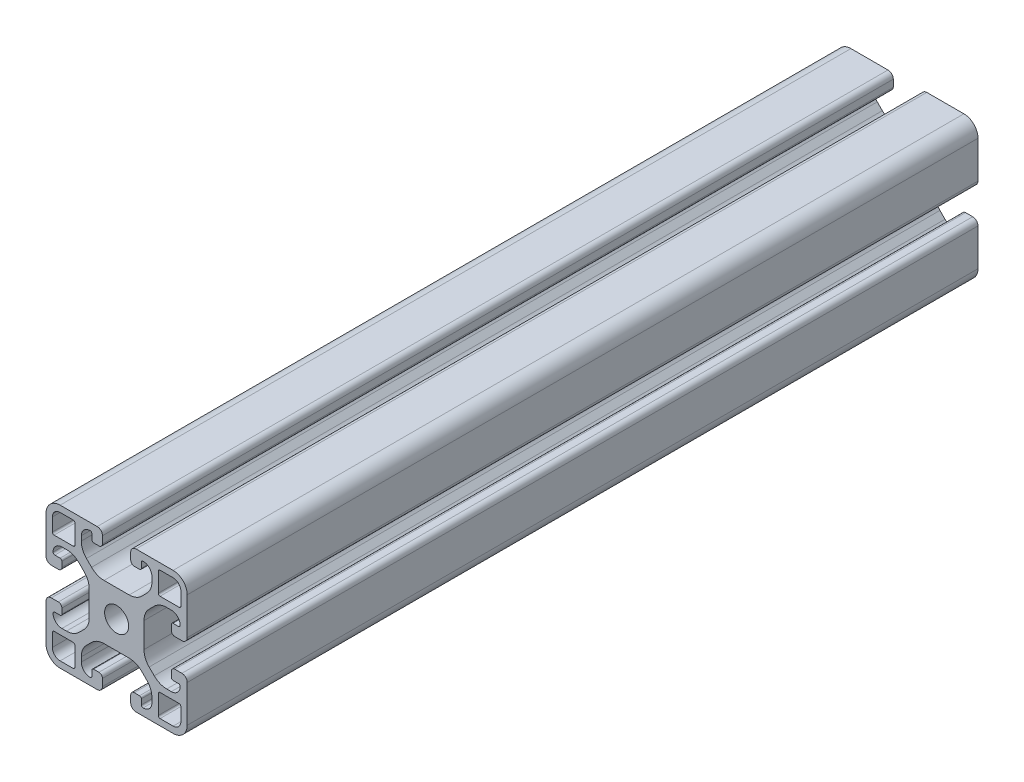
SolidWorks part; units mm, degrees
material "Alliage 1060"
ref_plane "Plan de face" through (0, 0, 0) normal (0, 0, 1) x (1, 0, 0)
ref_plane "Plan de dessus" through (0, 0, 0) normal (0, 1, 0) x (1, 0, 0)
ref_plane "Plan de droite" through (0, 0, 0) normal (1, 0, 0) x (0, 0, -1)
ref_plane "Plan1" through (0, 0, 20) normal (0, 0, 1) x (1, 0, 0)
sketch "Esquisse1" plane through (0, 0, 20) normal (0, 0, 1) x (1, 0, 0)
  line L0 (3.5, 16) -> (1.5, 16)
  line L1 (0, 14.5) -> (0, 4)
  line L2 (4, 0) -> (14.5, 0)
  line L3 (16, 1.5) -> (16, 3.5)
  line L4 (15, 4.5) -> (13.5, 4.5)
  line L5 (13, 4) -> (13, 2.5)
  line L6 (10, 4.5) -> (10, 5.8076)
  line L7 (11.4645, 9.3431) -> (12.9069, 10.7855)
  line L8 (16.4424, 12.25) -> (23.5576, 12.25)
  line L9 (27.0931, 10.7855) -> (28.5355, 9.3431)
  line L10 (30, 5.8076) -> (30, 4.5)
  line L11 (27, 2.5) -> (27, 4)
  line L12 (26.5, 4.5) -> (25, 4.5)
  line L13 (24, 3.5) -> (24, 1.5)
  line L14 (25.5, 0) -> (36, 0)
  line L15 (40, 4) -> (40, 14.5)
  line L16 (38.5, 16) -> (36.5, 16)
  line L17 (35.5, 15) -> (35.5, 13.5)
  line L18 (36, 13) -> (37.5, 13)
  line L19 (35.5, 10) -> (34.1924, 10)
  line L20 (30.6569, 11.4645) -> (29.2145, 12.9069)
  line L21 (27.75, 16.4424) -> (27.75, 23.5576)
  line L22 (29.2145, 27.0931) -> (30.6569, 28.5355)
  line L23 (34.1924, 30) -> (35.5, 30)
  line L24 (37.5, 27) -> (36, 27)
  line L25 (35.5, 26.5) -> (35.5, 25)
  line L26 (36.5, 24) -> (38.5, 24)
  line L27 (40, 25.5) -> (40, 36)
  line L28 (36, 40) -> (25.5, 40)
  line L29 (24, 38.5) -> (24, 36.5)
  line L30 (25, 35.5) -> (26.5, 35.5)
  line L31 (27, 36) -> (27, 37.5)
  line L32 (30, 35.5) -> (30, 34.1924)
  line L33 (28.5355, 30.6569) -> (27.0931, 29.2145)
  line L34 (23.5576, 27.75) -> (16.4424, 27.75)
  line L35 (12.9069, 29.2145) -> (11.4645, 30.6569)
  line L36 (10, 34.1924) -> (10, 35.5)
  line L37 (13, 37.5) -> (13, 36)
  line L38 (13.5, 35.5) -> (15, 35.5)
  line L39 (16, 36.5) -> (16, 38.5)
  line L40 (14.5, 40) -> (4, 40)
  line L41 (0, 36) -> (0, 25.5)
  line L42 (1.5, 24) -> (3.5, 24)
  line L43 (4.5, 25) -> (4.5, 26.5)
  line L44 (4, 27) -> (2.5, 27)
  line L45 (4.5, 30) -> (5.8076, 30)
  line L46 (9.3431, 28.5355) -> (10.7855, 27.0931)
  line L47 (12.25, 23.5576) -> (12.25, 16.4424)
  line L48 (10.7855, 12.9069) -> (9.3431, 11.4645)
  line L49 (5.8076, 10) -> (4.5, 10)
  line L50 (2.5, 13) -> (4, 13)
  line L51 (4.5, 13.5) -> (4.5, 15)
  line L52 (1.8, 4) -> (1.8, 7.7)
  line L53 (2.3, 8.2) -> (7.7, 8.2)
  line L54 (8.2, 7.7) -> (8.2, 2.3)
  line L55 (7.7, 1.8) -> (4, 1.8)
  line L56 (36, 1.8) -> (32.3, 1.8)
  line L57 (31.8, 2.3) -> (31.8, 7.7)
  line L58 (32.3, 8.2) -> (37.7, 8.2)
  line L59 (38.2, 7.7) -> (38.2, 4)
  line L60 (38.2, 36) -> (38.2, 32.3)
  line L61 (37.7, 31.8) -> (32.3, 31.8)
  line L62 (31.8, 32.3) -> (31.8, 37.7)
  line L63 (32.3, 38.2) -> (36, 38.2)
  line L64 (4, 38.2) -> (7.7, 38.2)
  line L65 (8.2, 37.7) -> (8.2, 32.3)
  line L66 (7.7, 31.8) -> (2.3, 31.8)
  line L67 (1.8, 32.3) -> (1.8, 36)
  arc A0 (4.5, 15) -> (3.5, 16) centre (3.5, 15) ccw
  arc A1 (1.5, 16) -> (0, 14.5) centre (1.5, 14.5) ccw
  arc A2 (0, 4) -> (4, 0) centre (4, 4) ccw
  arc A3 (14.5, 0) -> (16, 1.5) centre (14.5, 1.5) ccw
  arc A4 (16, 3.5) -> (15, 4.5) centre (15, 3.5) ccw
  arc A5 (13.5, 4.5) -> (13, 4) centre (13.5, 4) ccw
  arc A6 (13, 2.5) -> (12.5, 2) centre (12.5, 2.5) cw
  arc A7 (12.5, 2) -> (10, 4.5) centre (12.5, 4.5) cw
  arc A8 (10, 5.8076) -> (11.4645, 9.3431) centre (15, 5.8076) cw
  arc A9 (12.9069, 10.7855) -> (16.4424, 12.25) centre (16.4424, 7.25) cw
  arc A10 (23.5576, 12.25) -> (27.0931, 10.7855) centre (23.5576, 7.25) cw
  arc A11 (28.5355, 9.3431) -> (30, 5.8076) centre (25, 5.8076) cw
  arc A12 (30, 4.5) -> (27.5, 2) centre (27.5, 4.5) cw
  arc A13 (27.5, 2) -> (27, 2.5) centre (27.5, 2.5) cw
  arc A14 (27, 4) -> (26.5, 4.5) centre (26.5, 4) ccw
  arc A15 (25, 4.5) -> (24, 3.5) centre (25, 3.5) ccw
  arc A16 (24, 1.5) -> (25.5, 0) centre (25.5, 1.5) ccw
  arc A17 (36, 0) -> (40, 4) centre (36, 4) ccw
  arc A18 (40, 14.5) -> (38.5, 16) centre (38.5, 14.5) ccw
  arc A19 (36.5, 16) -> (35.5, 15) centre (36.5, 15) ccw
  arc A20 (35.5, 13.5) -> (36, 13) centre (36, 13.5) ccw
  arc A21 (37.5, 13) -> (38, 12.5) centre (37.5, 12.5) cw
  arc A22 (38, 12.5) -> (35.5, 10) centre (35.5, 12.5) cw
  arc A23 (34.1924, 10) -> (30.6569, 11.4645) centre (34.1924, 15) cw
  arc A24 (29.2145, 12.9069) -> (27.75, 16.4424) centre (32.75, 16.4424) cw
  arc A25 (27.75, 23.5576) -> (29.2145, 27.0931) centre (32.75, 23.5576) cw
  arc A26 (30.6569, 28.5355) -> (34.1924, 30) centre (34.1924, 25) cw
  arc A27 (35.5, 30) -> (38, 27.5) centre (35.5, 27.5) cw
  arc A28 (38, 27.5) -> (37.5, 27) centre (37.5, 27.5) cw
  arc A29 (36, 27) -> (35.5, 26.5) centre (36, 26.5) ccw
  arc A30 (35.5, 25) -> (36.5, 24) centre (36.5, 25) ccw
  arc A31 (38.5, 24) -> (40, 25.5) centre (38.5, 25.5) ccw
  arc A32 (40, 36) -> (36, 40) centre (36, 36) ccw
  arc A33 (25.5, 40) -> (24, 38.5) centre (25.5, 38.5) ccw
  arc A34 (24, 36.5) -> (25, 35.5) centre (25, 36.5) ccw
  arc A35 (26.5, 35.5) -> (27, 36) centre (26.5, 36) ccw
  arc A36 (27, 37.5) -> (27.5, 38) centre (27.5, 37.5) cw
  arc A37 (27.5, 38) -> (30, 35.5) centre (27.5, 35.5) cw
  arc A38 (30, 34.1924) -> (28.5355, 30.6569) centre (25, 34.1924) cw
  arc A39 (27.0931, 29.2145) -> (23.5576, 27.75) centre (23.5576, 32.75) cw
  arc A40 (16.4424, 27.75) -> (12.9069, 29.2145) centre (16.4424, 32.75) cw
  arc A41 (11.4645, 30.6569) -> (10, 34.1924) centre (15, 34.1924) cw
  arc A42 (10, 35.5) -> (12.5, 38) centre (12.5, 35.5) cw
  arc A43 (12.5, 38) -> (13, 37.5) centre (12.5, 37.5) cw
  arc A44 (13, 36) -> (13.5, 35.5) centre (13.5, 36) ccw
  arc A45 (15, 35.5) -> (16, 36.5) centre (15, 36.5) ccw
  arc A46 (16, 38.5) -> (14.5, 40) centre (14.5, 38.5) ccw
  arc A47 (4, 40) -> (0, 36) centre (4, 36) ccw
  arc A48 (0, 25.5) -> (1.5, 24) centre (1.5, 25.5) ccw
  arc A49 (3.5, 24) -> (4.5, 25) centre (3.5, 25) ccw
  arc A50 (4.5, 26.5) -> (4, 27) centre (4, 26.5) ccw
  arc A51 (2.5, 27) -> (2, 27.5) centre (2.5, 27.5) cw
  arc A52 (2, 27.5) -> (4.5, 30) centre (4.5, 27.5) cw
  arc A53 (5.8076, 30) -> (9.3431, 28.5355) centre (5.8076, 25) cw
  arc A54 (10.7855, 27.0931) -> (12.25, 23.5576) centre (7.25, 23.5576) cw
  arc A55 (12.25, 16.4424) -> (10.7855, 12.9069) centre (7.25, 16.4424) cw
  arc A56 (9.3431, 11.4645) -> (5.8076, 10) centre (5.8076, 15) cw
  arc A57 (4.5, 10) -> (2, 12.5) centre (4.5, 12.5) cw
  arc A58 (2, 12.5) -> (2.5, 13) centre (2.5, 12.5) cw
  arc A59 (4, 13) -> (4.5, 13.5) centre (4, 13.5) ccw
  circle A60 centre (20, 20) radius 3.4
  arc A61 (4, 1.8) -> (1.8, 4) centre (4, 4) cw
  arc A62 (1.8, 7.7) -> (2.3, 8.2) centre (2.3, 7.7) cw
  arc A63 (7.7, 8.2) -> (8.2, 7.7) centre (7.7, 7.7) cw
  arc A64 (8.2, 2.3) -> (7.7, 1.8) centre (7.7, 2.3) cw
  arc A65 (38.2, 4) -> (36, 1.8) centre (36, 4) cw
  arc A66 (32.3, 1.8) -> (31.8, 2.3) centre (32.3, 2.3) cw
  arc A67 (31.8, 7.7) -> (32.3, 8.2) centre (32.3, 7.7) cw
  arc A68 (37.7, 8.2) -> (38.2, 7.7) centre (37.7, 7.7) cw
  arc A69 (36, 38.2) -> (38.2, 36) centre (36, 36) cw
  arc A70 (38.2, 32.3) -> (37.7, 31.8) centre (37.7, 32.3) cw
  arc A71 (32.3, 31.8) -> (31.8, 32.3) centre (32.3, 32.3) cw
  arc A72 (31.8, 37.7) -> (32.3, 38.2) centre (32.3, 37.7) cw
  arc A73 (1.8, 36) -> (4, 38.2) centre (4, 36) cw
  arc A74 (7.7, 38.2) -> (8.2, 37.7) centre (7.7, 37.7) cw
  arc A75 (8.2, 32.3) -> (7.7, 31.8) centre (7.7, 32.3) cw
  arc A76 (2.3, 31.8) -> (1.8, 32.3) centre (2.3, 32.3) cw
extrude "Extrusion1" add sketch "Esquisse1" against normal blind 224
